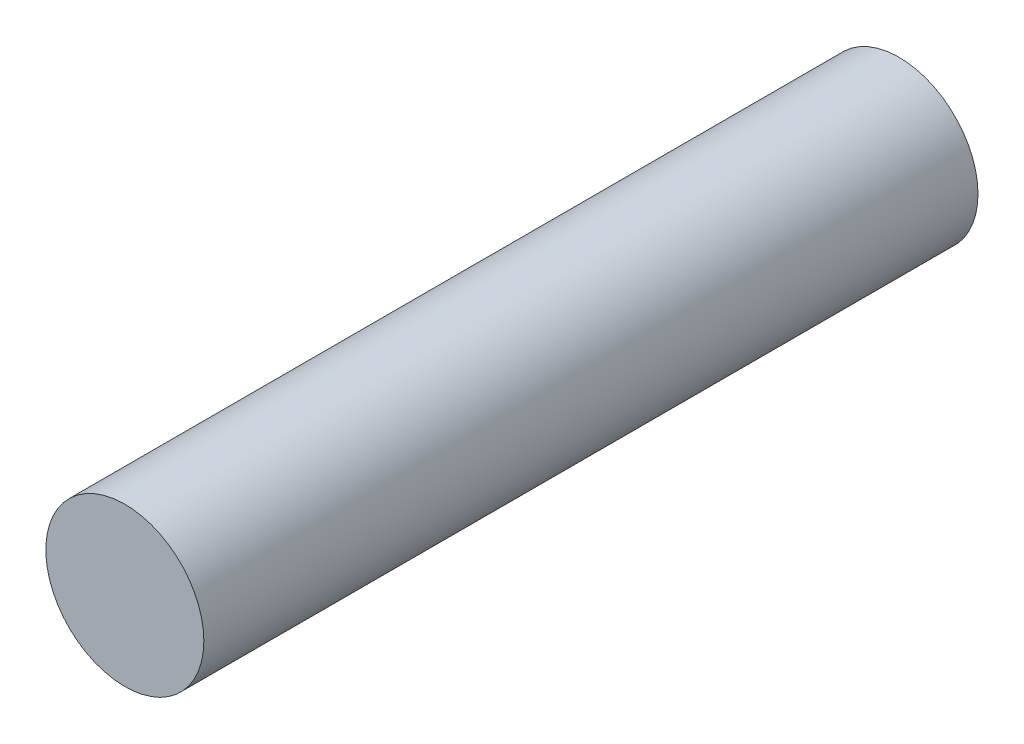
SolidWorks part; units mm, degrees
ref_plane "Front Plane" through (0, 0, 0) normal (0, 0, 1) x (1, 0, 0)
ref_plane "Top Plane" through (0, 0, 0) normal (0, 1, 0) x (1, 0, 0)
ref_plane "Right Plane" through (0, 0, 0) normal (1, 0, 0) x (0, 0, -1)
sketch "Sketch1" plane through (0, 0, 0) normal (0, 0, 1) x (1, 0, 0)
  circle A0 centre (0, 0) radius 1
  dimension "D1" = 2
extrude "Boss-Extrude1" add sketch "Sketch1" along normal blind 9.8
